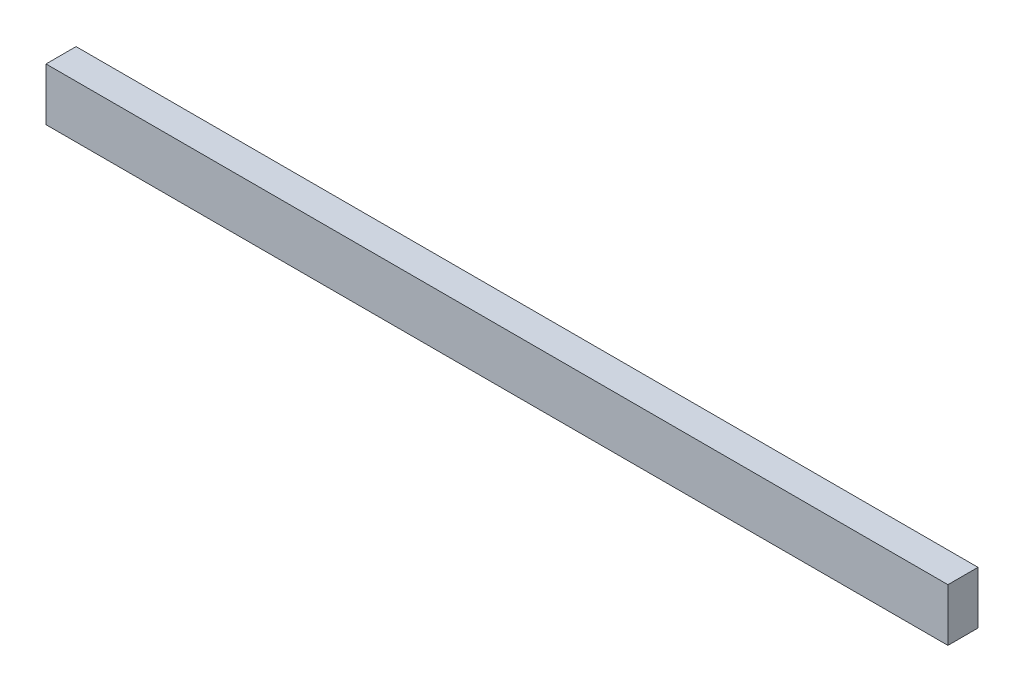
SolidWorks part; units mm, degrees
ref_plane "Front Plane" through (0, 0, 0) normal (0, 0, 1) x (1, 0, 0)
ref_plane "Top Plane" through (0, 0, 0) normal (0, 1, 0) x (1, 0, 0)
ref_plane "Right Plane" through (0, 0, 0) normal (1, 0, 0) x (0, 0, -1)
sketch "Sketch1" plane through (0, 0, 0) normal (0, 0, 1) x (1, 0, 0)
  line L1 (-255.9549, 102.6022) -> (48.8451, 102.6022)
  line L2 (-255.9549, 102.6022) -> (-255.9549, 84.8222)
  line L3 (-255.9549, 84.8222) -> (48.8451, 84.8222)
  line L4 (48.8451, 102.6022) -> (48.8451, 84.8222)
  dimension "D1" = 304.8
  dimension "D2" = 17.78
extrude "Boss-Extrude1" add sketch "Sketch1" along normal blind 10.16
